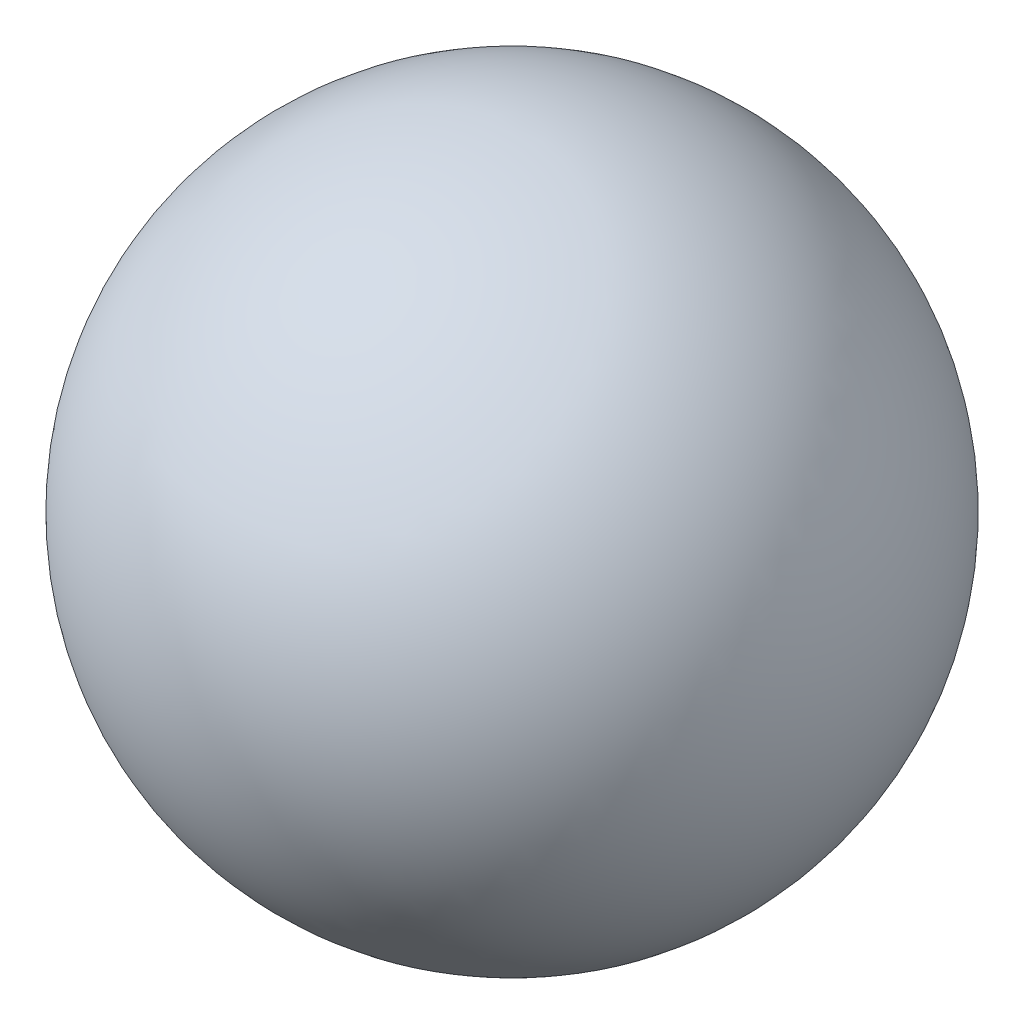
SolidWorks part; units mm, degrees
ref_plane "Plan de face" through (0, 0, 0) normal (0, 0, 1) x (1, 0, 0)
ref_plane "Plan de dessus" through (0, 0, 0) normal (0, 1, 0) x (1, 0, 0)
ref_plane "Plan de droite" through (0, 0, 0) normal (1, 0, 0) x (0, 0, -1)
sketch "Esquisse1" plane through (0, 0, 0) normal (0, 0, 1) x (1, 0, 0)
  line L0 (0, 10.2805) -> (0, -6.9143) construction
  line L1 (0, 6.4) -> (0, -6.4)
  arc A0 (0, 6.4) -> (0, -6.4) centre (0, 0) ccw
  dimension "D1" = 12.8
revolve "Révolution1" add sketch "Esquisse1" angle 360 about L1
